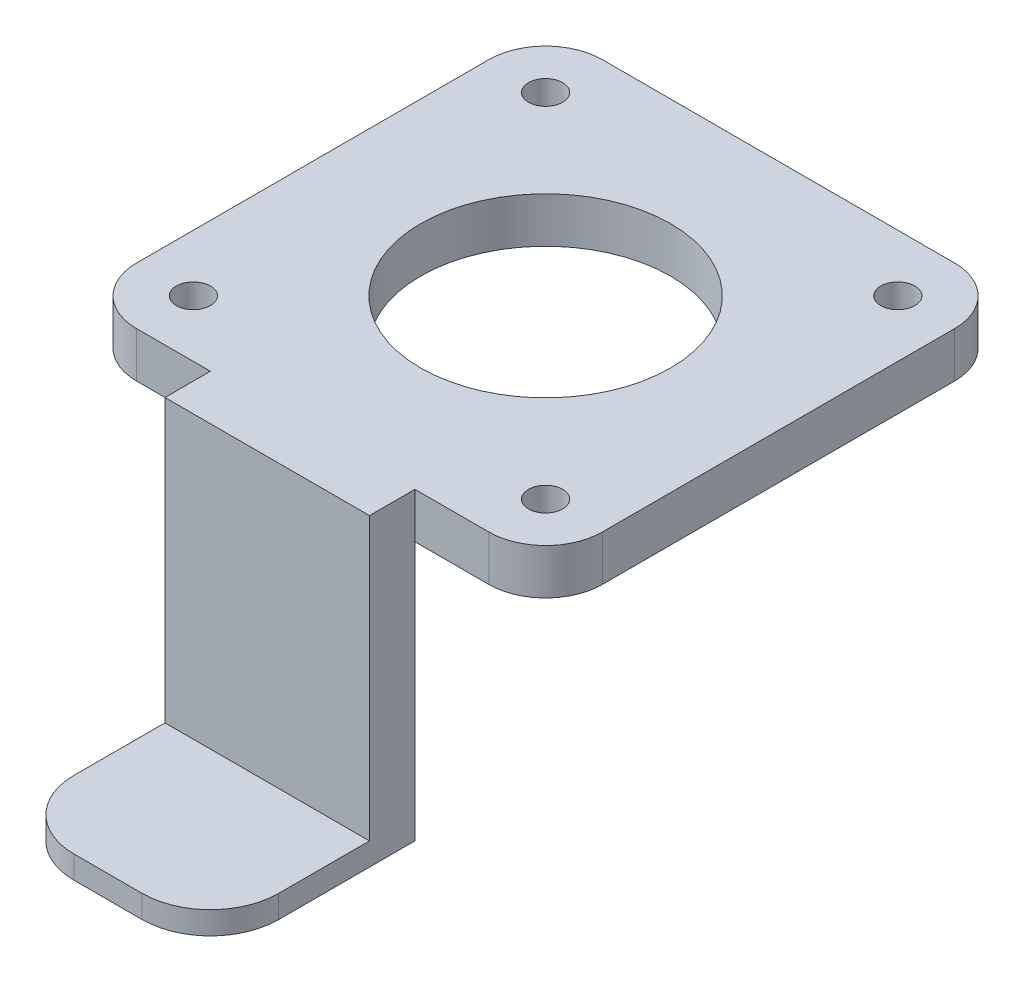
SolidWorks part; units mm, degrees
ref_plane "Спереди" through (0, 0, 0) normal (0, 0, 1) x (1, 0, 0)
ref_plane "Сверху" through (0, 0, 0) normal (0, 1, 0) x (1, 0, 0)
ref_plane "Справа" through (0, 0, 0) normal (1, 0, 0) x (0, 0, -1)
other "Configuration Table"
sketch "Эскиз2" plane through (0, 0, 0) normal (0, 1, 0) x (1, 0, 0)
  line L0 (0, 0) -> (-63.8997, 0) construction
  line L1 (-15.5, -20.5) -> (15.5, -20.5)
  line L2 (-20.5, -15.5) -> (-20.5, 15.5)
  line L3 (-15.5, 20.5) -> (15.5, 20.5)
  line L4 (20.5, -15.5) -> (20.5, 15.5)
  line L5 (-20.5, -20.5) -> (20.5, 20.5) construction
  line L6 (-20.5, 20.5) -> (20.5, -20.5) construction
  circle A0 centre (0, 0) radius 11
  circle A1 centre (-15.5, 15.5) radius 1.5
  circle A2 centre (15.5, -15.5) radius 1.5
  circle A3 centre (-15.5, -15.5) radius 1.5
  circle A4 centre (15.5, 15.5) radius 1.5
  arc A5 (-15.5, 20.5) -> (-20.5, 15.5) centre (-15.5, 15.5) ccw
  arc A6 (20.5, 15.5) -> (15.5, 20.5) centre (15.5, 15.5) ccw
  arc A7 (-15.5, -20.5) -> (-20.5, -15.5) centre (-15.5, -15.5) cw
  arc A8 (15.5, -20.5) -> (20.5, -15.5) centre (15.5, -15.5) ccw
  point P0 (0, 0)
  dimension "D3" = 22
  dimension "D4" = 3
  dimension "D7" = 5
  dimension "D8" = 5
  dimension "D9" = 5
  dimension "D10" = 5
  dimension "D1" = 41
  dimension "D2" = 41
  dimension "D5" = 31
  dimension "D6" = 31
extrude "дырка" add sketch "Эскиз2" along normal blind 4
sketch "Эскиз3" plane through (0, 0, 20.5) normal (0, 0, 1) x (1, 0, 0)
  line L0 (-15.5, 4) -> (15.5, 4) construction
  line L1 (-9, 4) -> (9, 4)
  line L2 (-9, 4) -> (-9, -22.8)
  line L3 (-9, -22.8) -> (9, -22.8)
  line L4 (9, 4) -> (9, -22.8)
  line L5 (-20.5, 4) -> (-20.5, 0) construction
  dimension "D1" = 18
  dimension "D2" = 11.5
  dimension "D3" = 26.8
  dimension "D4" = 26.8
extrude "нога" add sketch "Эскиз3" along normal blind 4 contours L1 L4 L3 L2
sketch "Эскиз4" plane through (0, -22.8, 0) normal (0, -1, 0) x (1, 0, 0)
  line L1 (9, 24.5) -> (-9, 24.5)
  line L2 (9, 24.5) -> (9, 32.5)
  line L3 (3, 38.5) -> (-3, 38.5)
  line L4 (-9, 24.5) -> (-9, 32.5)
  arc A0 (-3, 38.5) -> (-9, 32.5) centre (-3, 32.5) ccw
  arc A1 (3, 38.5) -> (9, 32.5) centre (3, 32.5) cw
  point P7 (-9, 38.5)
  dimension "D2" = 6
  dimension "D3" = 6
  dimension "D1" = 14
extrude "нога с дыркой" add sketch "Эскиз4" against normal blind 2
